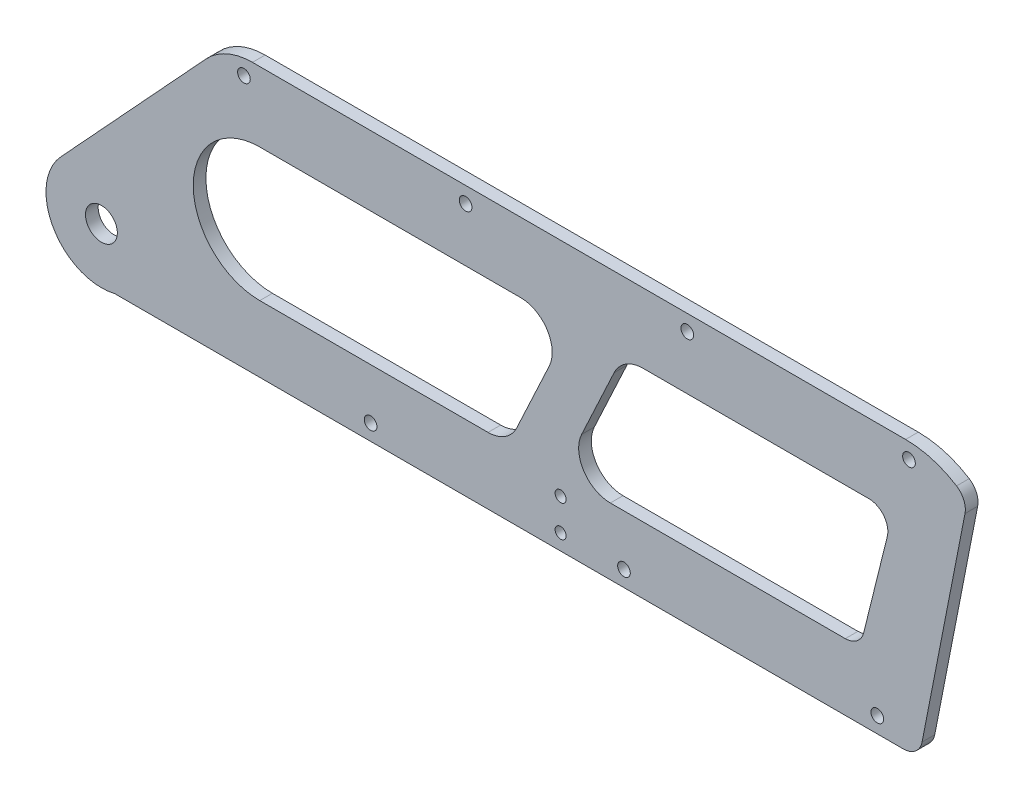
SolidWorks part; units mm, degrees
ref_plane "前视基准面" through (0, 0, 0) normal (0, 0, 1) x (1, 0, 0)
ref_plane "上视基准面" through (0, 0, 0) normal (0, 1, 0) x (1, 0, 0)
ref_plane "右视基准面" through (0, 0, 0) normal (1, 0, 0) x (0, 0, -1)
sketch "草图2" plane through (0, 0, 0) normal (0, 0, 1) x (1, 0, 0)
  line L0 (-262.3052, 68) -> (-56.0638, 68)
  line L1 (-149.3031, 4) -> (-60, 4) construction
  line L2 (-67.6705, 46) -> (-139.0444, 46)
  line L3 (-148.1075, 40.2262) -> (-158.3662, 18.2262)
  line L6 (-178.8583, 9.7738) -> (-168.5995, 31.7738)
  line L7 (-260, 4) -> (-187.9214, 4)
  line L8 (-177.6626, 46) -> (-260, 46)
  line L9 (-322.861, 11.8678) -> (-277.0035, 61.5632)
  line L12 (-56.7504, -17) -> (-305.8467, -17)
  line L13 (-50.8621, -12.1521) -> (-37.3109, 57.1088)
  line L15 (-61.847, 38.5552) -> (-69.29, 8.5552)
  line L16 (-149.3031, 4) -> (-75.1135, 4)
  circle A0 centre (-55, 63) radius 2
  circle A1 centre (-195, 63) radius 2
  circle A3 centre (-265, 63) radius 2
  circle A4 centre (-225, -12) radius 2
  circle A5 centre (-65, -12) radius 2
  circle A6 centre (-310, 0) radius 5.03
  circle A7 centre (-125, 63) radius 2
  circle A8 centre (-145, -12) radius 2
  circle A11 centre (-165, -2) radius 1.75
  circle A12 centre (-165, -12) radius 1.75
  arc A17 (-39.9831, 63.3261) -> (-56.0638, 68) centre (-56.0638, 38) ccw
  arc A18 (-262.3052, 68) -> (-277.0035, 61.5632) centre (-262.3052, 48) ccw
  arc A19 (-158.3662, 18.2262) -> (-149.3031, 4) centre (-149.3031, 14) ccw
  arc A20 (-60, 4) -> (-60, 46) centre (-60, 25) ccw construction
  arc A21 (-139.0444, 46) -> (-148.1075, 40.2262) centre (-139.0444, 36) ccw
  arc A22 (-322.861, 11.8678) -> (-305.8467, -17) centre (-310, 0) ccw
  arc A24 (-187.9214, 4) -> (-178.8583, 9.7738) centre (-187.9214, 14) ccw
  arc A25 (-260, 46) -> (-260, 4) centre (-260, 25) ccw
  arc A26 (-168.5995, 31.7738) -> (-177.6626, 46) centre (-177.6626, 36) ccw
  circle A34 centre (-60, 25) radius 42.791 construction
  arc A35 (-36.5854, 60.8165) -> (-51.8106, -17) centre (-60, 25) cw construction
  arc A36 (-56.7504, -17) -> (-50.8621, -12.1521) centre (-56.7504, -11) ccw
  arc A37 (-37.3109, 57.1088) -> (-39.9831, 63.3261) centre (-43.1992, 58.2609) ccw
  arc A38 (-61.847, 38.5552) -> (-67.6705, 46) centre (-67.6705, 40) ccw
  arc A39 (-69.29, 8.5552) -> (-75.1135, 4) centre (-75.1135, 10) cw
  point P35 (-70.4202, 4)
  point P36 (0, 0)
  dimension "D1" = 6
  dimension "D2" = 6
extrude "凸台-拉伸1" add sketch "草图2" along normal blind 4 separate body contours L0 A17 A22 L9 A18
